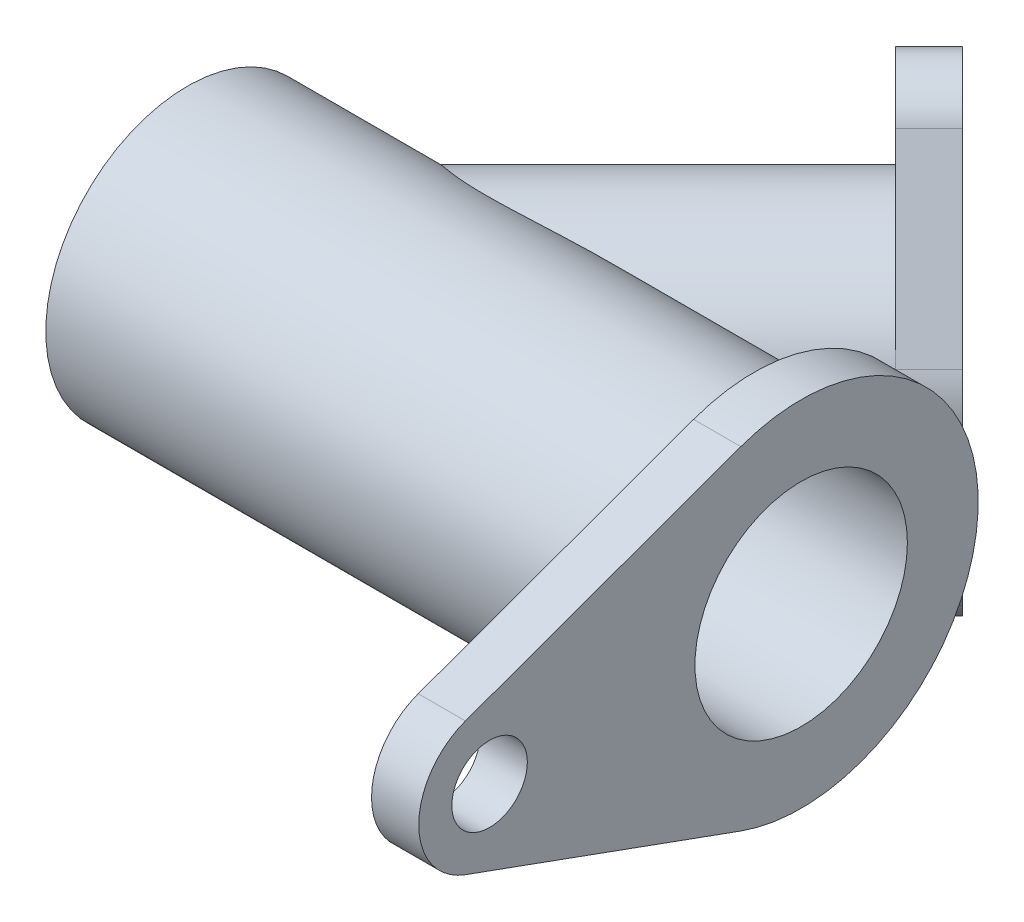
SolidWorks part; units mm, degrees
ref_plane "前视基准面" through (0, 0, 0) normal (0, 0, 1) x (1, 0, 0)
ref_plane "上视基准面" through (0, 0, 0) normal (0, 1, 0) x (1, 0, 0)
ref_plane "右视基准面" through (0, 0, 0) normal (1, 0, 0) x (0, 0, -1)
sketch "草图1" plane through (0, 0, 0) normal (1, 0, 0) x (0, 0, -1)
  line L0 (118.2355, 0) -> (-145.2943, 0) construction
  line L1 (0, 117.5227) -> (0, -124.8007) construction
  circle A0 centre (0, 0) radius 45
  circle A1 centre (0, 0) radius 60
  point P9 (60, 0)
  dimension "D1" = 90
  dimension "D2" = 120
extrude "凸台-拉伸1" add sketch "草图1" along normal blind 240
sketch "草图2" plane through (240, 0, 0) normal (1, 0, 0) x (0, 0, -1)
  line L0 (-143.9697, 0) -> (143.9697, 0) construction
  line L1 (0, 89.5599) -> (0, -89.5599) construction
  line L2 (-142.2273, 28.2029) -> (-25.5682, 70.5072)
  line L3 (-142.2273, -28.2029) -> (-25.5682, -70.5072)
  circle A0 centre (0, 0) radius 45
  arc A1 (-25.5682, -70.5072) -> (-25.5682, 70.5072) centre (0, 0) ccw
  circle A2 centre (0, 0) radius 45 construction
  circle A3 centre (-132, 0) radius 16
  arc A4 (-142.2273, 28.2029) -> (-142.2273, -28.2029) centre (-132, 0) ccw
  dimension "D1" = 75
  dimension "D2" = 32
  dimension "D4" = 30
  dimension "D3" = 132
extrude "凸台-拉伸2" add sketch "草图2" along normal blind 20
sketch "草图10" plane through (260, 0, 0) normal (1, 0, 0) x (0, 0, -1)
  line L0 (0, 0) -> (-185.5456, 0) construction
  line L1 (0, 0) -> (0, 213.8395) construction
  point P3 (0, 0)
ref_plane "基准面6" through (0, 0, 0) normal (0, 1, 0) x (1, 0, 0)
sketch "草图11" plane through (0, 0, 0) normal (0, 1, 0) x (1, 0, 0)
  point P0 (180, 120)
  point P1 (260, 0)
  dimension "D1" = 120
  dimension "D2" = 80
sketch "草图13" plane through (0, 0, 0) normal (-1, 0, 0) x (0, 0, 1)
  circle A0 centre (0, 0) radius 60 construction
  point P0 (-60, 0)
ref_plane "基准面7" through (0, 0, -60) normal (0, 0, -1) x (-1, 0, 0)
sketch "草图14" plane through (0, 0, -60) normal (0, 0, -1) x (-1, 0, 0)
  line L0 (-116.5789, 51.3703) -> (-116.5789, -59.9527) construction
  point P2 (0, 0)
ref_plane "基准面8" through (88.2895, 0, -88.2895) normal (0.7071, 0, -0.7071) x (0, -1, 0)
ref_plane "基准面9" through (150, 0, -150) normal (0.7071, 0, -0.7071) x (-0.7071, 0, -0.7071)
sketch "草图15" plane through (150, 0, -150) normal (0.7071, 0, -0.7071) x (-0.7071, 0, -0.7071)
  circle A0 centre (-42.4264, 0) radius 50
  circle A1 centre (-42.4264, 0) radius 30
  dimension "D1" = 100
  dimension "D2" = 60
extrude "凸台-拉伸4" add sketch "草图15" against normal up to next
sketch "草图18" plane through (150, 0, -150) normal (0.7071, 0, -0.7071) x (-0.7071, 0, -0.7071)
  circle A0 centre (-42.4264, 0) radius 30
  circle A1 centre (-42.4264, 0) radius 30 construction
extrude "切除-拉伸1" cut sketch "草图18" against normal up to next
sketch "草图19" plane through (150, 0, -150) normal (0.7071, 0, -0.7071) x (-0.7071, 0, -0.7071)
  line L4 (-244.0867, 0) -> (159.2339, 0) construction
  line L5 (-42.4264, 177.584) -> (-42.4264, -177.584) construction
  line L6 (-60.9669, 87.5) -> (-88.7776, 18.75)
  line L7 (-23.8859, 87.5) -> (3.9248, 18.75)
  line L8 (-60.9669, -87.5) -> (-88.7776, -18.75)
  line L9 (-23.8859, -87.5) -> (3.9248, -18.75)
  circle A0 centre (-42.4264, 0) radius 30
  circle A1 centre (-42.4264, 0) radius 30 construction
  arc A2 (-88.7776, 18.75) -> (-88.7776, -18.75) centre (-42.4264, 0) ccw
  circle A3 centre (-42.4264, 0) radius 50 construction
  arc A4 (-23.8859, 87.5) -> (-60.9669, 87.5) centre (-42.4264, 80) ccw
  arc A5 (-60.9669, -87.5) -> (-23.8859, -87.5) centre (-42.4264, -80) ccw
  arc A6 (3.9248, -18.75) -> (3.9248, 18.75) centre (-42.4264, 0) ccw
  circle A7 centre (-42.4264, 80) radius 10
  circle A8 centre (-42.4264, -80) radius 10
  point P9 (-60.9669, -87.5)
  point P14 (-88.7776, -18.75)
  point P23 (3.9248, -18.75)
  point P24 (-23.8859, -87.5)
  dimension "D1" = 40
  dimension "D3" = 20
  dimension "D4" = 20
  dimension "D2" = 160
extrude "凸台-拉伸6" add sketch "草图19" along normal blind 20
